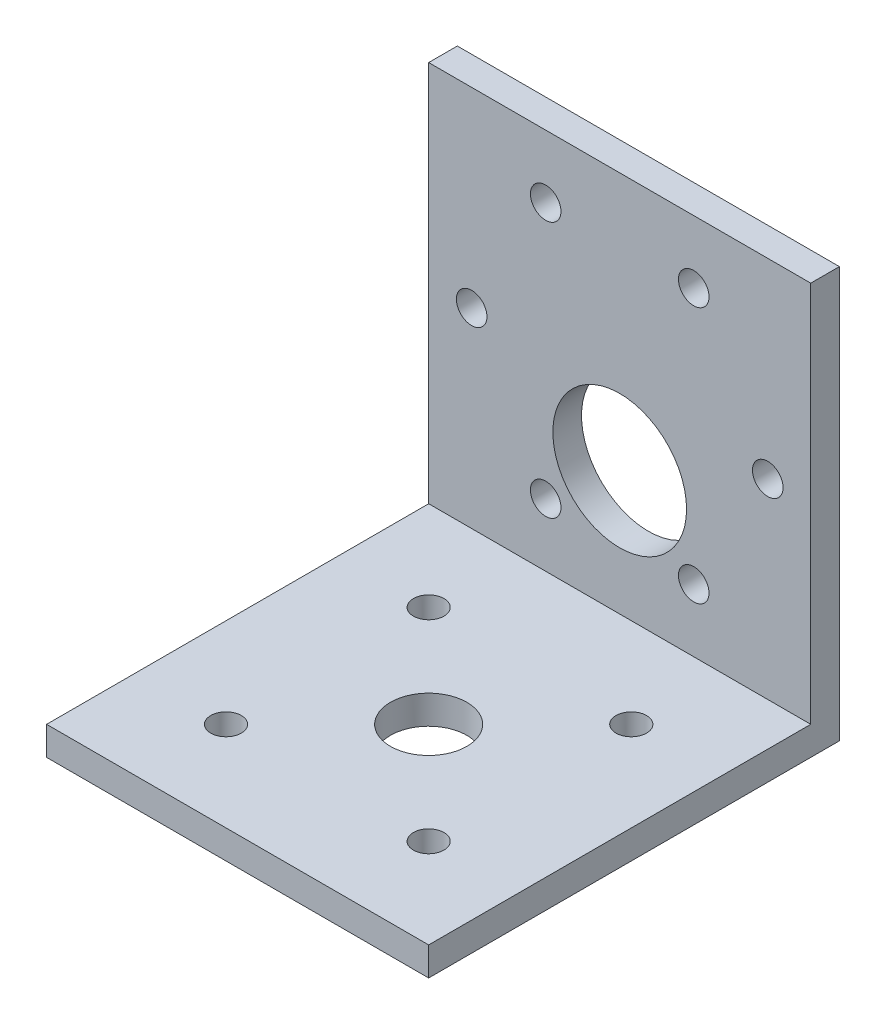
SolidWorks part; units mm, degrees
ref_plane "Front Plane" through (0, 0, 0) normal (0, 0, 1) x (1, 0, 0)
ref_plane "Top Plane" through (0, 0, 0) normal (0, 1, 0) x (1, 0, 0)
ref_plane "Right Plane" through (0, 0, 0) normal (1, 0, 0) x (0, 0, -1)
sketch "Sketch2" plane through (0, 0, 0) normal (0, 0, 1) x (1, 0, 0)
  line L0 (47.0148, -20) -> (-7.0148, -20) construction
  line L1 (0, 0) -> (40, 0)
  line L2 (0, 0) -> (0, -40)
  line L3 (0, -40) -> (40, -40)
  line L4 (40, 0) -> (40, -40)
  line L5 (20, -20) -> (20, -27) construction
  circle A0 centre (4.5, -20) radius 1.6
  circle A1 centre (35.5, -20) radius 1.6
  circle A3 centre (12.25, -6.5766) radius 1.6
  circle A4 centre (27.75, -6.5766) radius 1.6
  circle A5 centre (27.75, -33.4234) radius 1.6
  circle A6 centre (12.25, -33.4234) radius 1.6
  circle A7 centre (20, -27) radius 7
  dimension "D2" = 7
  dimension "D3" = 3.2
  dimension "D5" = 14
  dimension "D1" = 40
  dimension "D4" = 15.5
  dimension "D6" = 20
  dimension "D7" = 40
extrude "Boss-Extrude1" add sketch "Sketch2" along normal blind 3
sketch "Sketch3" plane through (0, 0, 0) normal (1, 0, 0) x (0, 0, -1)
  line L1 (0, -40) -> (-43, -40)
  line L2 (0, -40) -> (0, -43)
  line L3 (0, -43) -> (-43, -43)
  line L4 (-43, -40) -> (-43, -43)
  dimension "D1" = 3
  dimension "D2" = 43
extrude "Boss-Extrude2" add sketch "Sketch3" along normal up to surface (40 mm away) up to face at (40, -20, 1.5)
sketch "Sketch4" plane through (0, -40, 0) normal (0, 1, 0) x (1, 0, 0)
  line L0 (20, -3) -> (20, -43) construction
  line L1 (0, -3) -> (40, -3) construction
  line L2 (40, -43) -> (0, -43) construction
  line L4 (0, -3) -> (0, -43) construction
  line L6 (40, -3) -> (0, -43) construction
  circle A0 centre (9.3934, -33.6066) radius 1.6
  circle A1 centre (20, -23) radius 4
  circle A2 centre (9.3934, -12.3934) radius 1.6
  circle A3 centre (30.6066, -12.3934) radius 1.6
  circle A4 centre (30.6066, -33.6066) radius 1.6
  point P14 (20, -23)
  point P25 (20, -23)
  dimension "D3" = 8
  dimension "D4" = 3.2
  dimension "D1" = 15
  dimension "D2" = 4
extrude "Cut-Extrude1" cut sketch "Sketch4" against normal through all both and the other way through all
